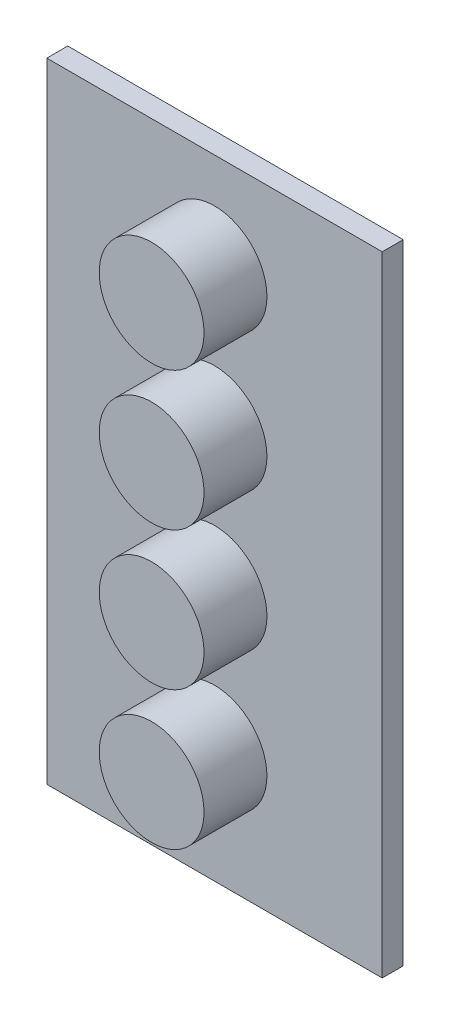
SolidWorks part; units mm, degrees
ref_plane "Ön Düzlem" through (0, 0, 0) normal (0, 0, 1) x (1, 0, 0)
ref_plane "Üst Düzlem" through (0, 0, 0) normal (0, 1, 0) x (1, 0, 0)
ref_plane "Sağ Düzlem" through (0, 0, 0) normal (1, 0, 0) x (0, 0, -1)
sketch "Sketch1" plane through (0, 0, 0) normal (0, 0, 1) x (1, 0, 0)
  line L1 (-40, 75) -> (40, 75)
  line L2 (-40, 75) -> (-40, -75)
  line L3 (-40, -75) -> (40, -75)
  line L4 (40, 75) -> (40, -75)
  line L5 (-40, 75) -> (40, -75) construction
  line L6 (-40, -75) -> (40, 75) construction
  point P0 (0, 0)
  dimension "D1" = 150
  dimension "D2" = 80
extrude "Boss-Extrude1" add sketch "Sketch1" along normal blind 5
sketch "Sketch2" plane through (0, 0, 5) normal (0, 0, 1) x (1, 0, 0)
  line L0 (40, 75) -> (-40, 75) construction
  circle A0 centre (0, 51.9812) radius 12.5
  circle A1 centre (0, 18.9812) radius 12.5
  circle A2 centre (0, -14.0188) radius 12.5
  circle A3 centre (0, -47.0188) radius 12.5
  point P5 (0, 75)
  dimension "D2" = 25
  dimension "D1" = 4
extrude "Boss-Extrude2" add sketch "Sketch2" along normal blind 15
